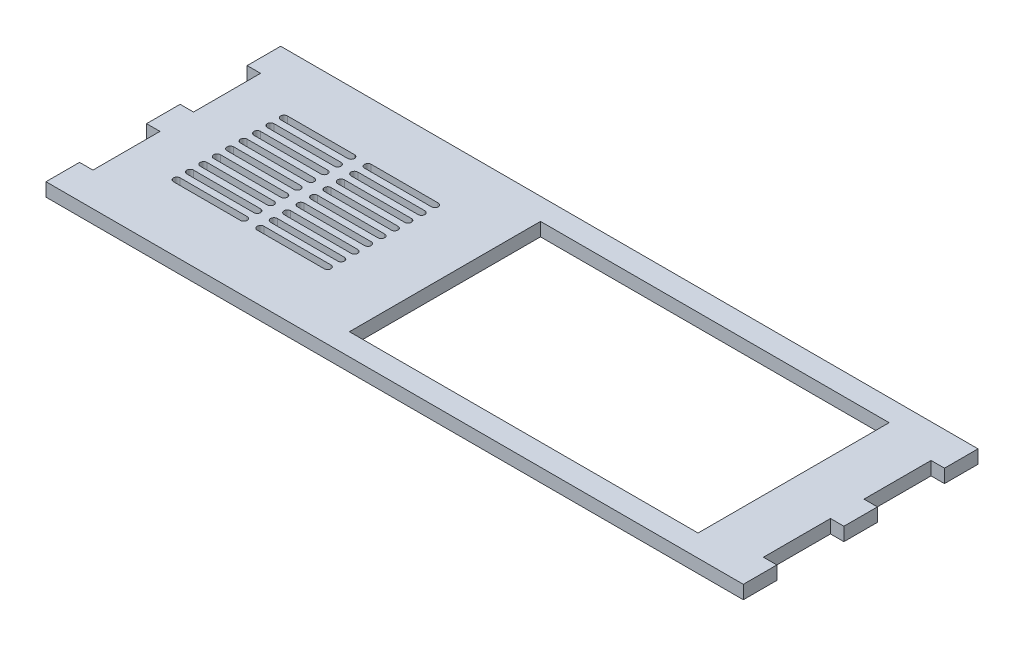
SolidWorks part; units mm, degrees
ref_plane "Front Plane" through (0, 0, 0) normal (0, 0, 1) x (1, 0, 0)
ref_plane "Top Plane" through (0, 0, 0) normal (0, 1, 0) x (1, 0, 0)
ref_plane "Right Plane" through (0, 0, 0) normal (1, 0, 0) x (0, 0, -1)
sketch "Sketch1" plane through (0, 0, 0) normal (0, 1, 0) x (1, 0, 0)
  line L0 (35, 20) -> (15, 20) construction
  line L1 (0, 0) -> (200, 0)
  line L2 (0, 0) -> (0, 70)
  line L3 (0, 70) -> (200, 70)
  line L4 (200, 0) -> (200, 70)
  line L5 (0, 70) -> (-4, 70)
  line L6 (0, 70) -> (0, 60)
  line L7 (0, 60) -> (-4, 60)
  line L8 (-4, 70) -> (-4, 60)
  line L9 (0, 0) -> (-4, 0)
  line L10 (0, 0) -> (0, 10)
  line L11 (0, 10) -> (-4, 10)
  line L12 (-4, 0) -> (-4, 10)
  line L13 (200, 0) -> (204, 0)
  line L14 (200, 0) -> (200, 10)
  line L15 (200, 10) -> (204, 10)
  line L16 (204, 0) -> (204, 10)
  line L17 (200, 70) -> (204, 70)
  line L18 (200, 70) -> (200, 60)
  line L19 (200, 60) -> (204, 60)
  line L20 (204, 70) -> (204, 60)
  line L21 (0, 40) -> (-4, 40)
  line L22 (0, 40) -> (0, 30)
  line L23 (0, 30) -> (-4, 30)
  line L24 (-4, 40) -> (-4, 30)
  line L25 (200, 40) -> (204, 40)
  line L26 (200, 40) -> (200, 30)
  line L27 (200, 30) -> (204, 30)
  line L28 (204, 40) -> (204, 30)
  line L29 (80, 63.5) -> (184, 63.5)
  line L30 (80, 63.5) -> (80, 6.5)
  line L31 (80, 6.5) -> (184, 6.5)
  line L32 (184, 63.5) -> (184, 6.5)
  line L33 (35, 19) -> (15, 19)
  line L34 (35, 21) -> (15, 21)
  line L35 (60, 20) -> (40, 20) construction
  line L36 (60, 19) -> (40, 19)
  line L37 (60, 21) -> (40, 21)
  line L38 (35, 24) -> (15, 24) construction
  line L39 (35, 23) -> (15, 23)
  line L40 (35, 25) -> (15, 25)
  line L41 (60, 24) -> (40, 24) construction
  line L42 (60, 23) -> (40, 23)
  line L43 (60, 25) -> (40, 25)
  line L44 (35, 28) -> (15, 28) construction
  line L45 (35, 27) -> (15, 27)
  line L46 (35, 29) -> (15, 29)
  line L47 (60, 28) -> (40, 28) construction
  line L48 (60, 27) -> (40, 27)
  line L49 (60, 29) -> (40, 29)
  line L50 (35, 32) -> (15, 32) construction
  line L51 (35, 31) -> (15, 31)
  line L52 (35, 33) -> (15, 33)
  line L53 (60, 32) -> (40, 32) construction
  line L54 (60, 31) -> (40, 31)
  line L55 (60, 33) -> (40, 33)
  line L56 (35, 36) -> (15, 36) construction
  line L57 (35, 35) -> (15, 35)
  line L58 (35, 37) -> (15, 37)
  line L59 (60, 36) -> (40, 36) construction
  line L60 (60, 35) -> (40, 35)
  line L61 (60, 37) -> (40, 37)
  line L62 (35, 40) -> (15, 40) construction
  line L63 (35, 39) -> (15, 39)
  line L64 (35, 41) -> (15, 41)
  line L65 (60, 40) -> (40, 40) construction
  line L66 (60, 39) -> (40, 39)
  line L67 (60, 41) -> (40, 41)
  line L68 (35, 44) -> (15, 44) construction
  line L69 (35, 43) -> (15, 43)
  line L70 (35, 45) -> (15, 45)
  line L71 (60, 44) -> (40, 44) construction
  line L72 (60, 43) -> (40, 43)
  line L73 (60, 45) -> (40, 45)
  line L74 (35, 48) -> (15, 48) construction
  line L75 (35, 47) -> (15, 47)
  line L76 (35, 49) -> (15, 49)
  line L77 (60, 48) -> (40, 48) construction
  line L78 (60, 47) -> (40, 47)
  line L79 (60, 49) -> (40, 49)
  line L80 (35, 52) -> (15, 52) construction
  line L81 (35, 51) -> (15, 51)
  line L82 (35, 53) -> (15, 53)
  line L83 (60, 52) -> (40, 52) construction
  line L84 (60, 51) -> (40, 51)
  line L85 (60, 53) -> (40, 53)
  arc A0 (35, 19) -> (35, 21) centre (35, 20) ccw
  arc A1 (15, 21) -> (15, 19) centre (15, 20) ccw
  arc A2 (60, 19) -> (60, 21) centre (60, 20) ccw
  arc A3 (40, 21) -> (40, 19) centre (40, 20) ccw
  arc A4 (35, 23) -> (35, 25) centre (35, 24) ccw
  arc A5 (15, 25) -> (15, 23) centre (15, 24) ccw
  arc A6 (60, 23) -> (60, 25) centre (60, 24) ccw
  arc A7 (40, 25) -> (40, 23) centre (40, 24) ccw
  arc A8 (35, 27) -> (35, 29) centre (35, 28) ccw
  arc A9 (15, 29) -> (15, 27) centre (15, 28) ccw
  arc A10 (60, 27) -> (60, 29) centre (60, 28) ccw
  arc A11 (40, 29) -> (40, 27) centre (40, 28) ccw
  arc A12 (35, 31) -> (35, 33) centre (35, 32) ccw
  arc A13 (15, 33) -> (15, 31) centre (15, 32) ccw
  arc A14 (60, 31) -> (60, 33) centre (60, 32) ccw
  arc A15 (40, 33) -> (40, 31) centre (40, 32) ccw
  arc A16 (35, 35) -> (35, 37) centre (35, 36) ccw
  arc A17 (15, 37) -> (15, 35) centre (15, 36) ccw
  arc A18 (60, 35) -> (60, 37) centre (60, 36) ccw
  arc A19 (40, 37) -> (40, 35) centre (40, 36) ccw
  arc A20 (35, 39) -> (35, 41) centre (35, 40) ccw
  arc A21 (15, 41) -> (15, 39) centre (15, 40) ccw
  arc A22 (60, 39) -> (60, 41) centre (60, 40) ccw
  arc A23 (40, 41) -> (40, 39) centre (40, 40) ccw
  arc A24 (35, 43) -> (35, 45) centre (35, 44) ccw
  arc A25 (15, 45) -> (15, 43) centre (15, 44) ccw
  arc A26 (60, 43) -> (60, 45) centre (60, 44) ccw
  arc A27 (40, 45) -> (40, 43) centre (40, 44) ccw
  arc A28 (35, 47) -> (35, 49) centre (35, 48) ccw
  arc A29 (15, 49) -> (15, 47) centre (15, 48) ccw
  arc A30 (60, 47) -> (60, 49) centre (60, 48) ccw
  arc A31 (40, 49) -> (40, 47) centre (40, 48) ccw
  arc A32 (35, 51) -> (35, 53) centre (35, 52) ccw
  arc A33 (15, 53) -> (15, 51) centre (15, 52) ccw
  arc A34 (60, 51) -> (60, 53) centre (60, 52) ccw
  arc A35 (40, 53) -> (40, 51) centre (40, 52) ccw
  point P31 (25, 20)
  point P40 (50, 20)
  point P47 (25, 24)
  point P54 (50, 24)
  point P61 (25, 28)
  point P68 (50, 28)
  point P75 (25, 32)
  point P82 (50, 32)
  point P89 (25, 36)
  point P96 (50, 36)
  point P103 (25, 40)
  point P110 (50, 40)
  point P117 (25, 44)
  point P124 (50, 44)
  point P131 (25, 48)
  point P138 (50, 48)
  point P145 (25, 52)
  point P152 (50, 52)
  dimension "D21" = 20
  dimension "D1" = 70
  dimension "D2" = 200
  dimension "D3" = 10
  dimension "D4" = 10
  dimension "D5" = 4
  dimension "D6" = 4
  dimension "D7" = 10
  dimension "D8" = 4
  dimension "D9" = 10
  dimension "D10" = 4
  dimension "D11" = 10
  dimension "D12" = 4
  dimension "D13" = 20
  dimension "D14" = 10
  dimension "D15" = 20
  dimension "D16" = 57
  dimension "D17" = 104
  dimension "D18" = 80
  dimension "D19" = 6.5
  dimension "D20" = 2
  dimension "D22" = 15
  dimension "D23" = 20
  dimension "D24" = 2
  dimension "D25" = 9
extrude "Boss-Extrude1" add sketch "Sketch1" along normal blind 4 contours L1 L4 L3 L2 L29 L32 L31 L30 | L21 L24 L23 L22 | L9 L12 L11 L10 | L5 L8 L7 L6 | L13 L16 L15 L14 | L28 L27 L26 L25 | L17 L20 L19 L18
